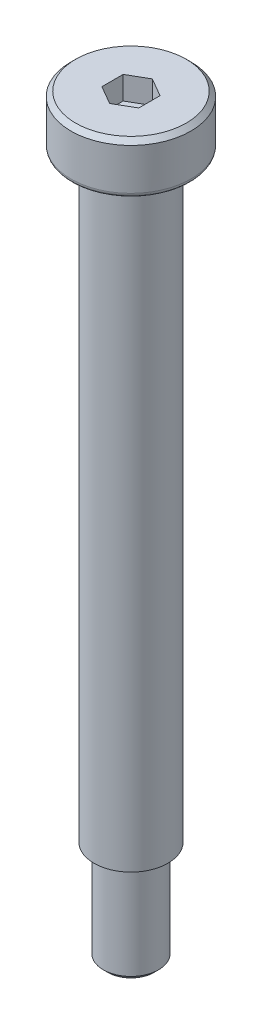
SolidWorks part; units mm, degrees
material "Plain Carbon Steel"
ref_plane "Front Plane" through (0, 0, 0) normal (0, 0, 1) x (1, 0, 0)
ref_plane "Top Plane" through (0, 0, 0) normal (0, 1, 0) x (1, 0, 0)
ref_plane "Right Plane" through (0, 0, 0) normal (1, 0, 0) x (0, 0, -1)
sketch "Sketch1" plane through (0, 0, 0) normal (0, 0, 1) x (1, 0, 0)
  line L0 (0, 0) -> (6.5, 0)
  line L1 (6.5, 0) -> (6.5, -5.5)
  line L2 (6.5, -5.5) -> (3.75, -5.5)
  line L3 (3.75, -5.5) -> (3.75, -5.75)
  line L4 (3.75, -5.75) -> (4, -5.75)
  line L5 (4, -5.75) -> (4, -70.5)
  line L6 (4, -70.5) -> (3, -70.5)
  line L7 (3, -70.5) -> (3, -81.5)
  line L8 (3, -81.5) -> (0, -81.5)
  line L9 (0, -81.5) -> (0, 0)
  line L10 (0, 5) -> (0, -86.5) construction
  dimension "D1" = 5
  dimension "D2" = 5
  dimension "D3" = 6
  dimension "D4" = 8
  dimension "D5" = 0.25
  dimension "D6" = 13
  dimension "Length" = 65
  dimension "D8" = 5.5
  dimension "D9" = 0.25
  dimension "D10" = 11
revolve "Revolve1" add sketch "Sketch1" angle 360 about L10
sketch "Sketch2" plane through (0, 0, 0) normal (0, 1, 0) x (1, 0, 0)
  line L1 (0, -2.3094) -> (2, -1.1547)
  line L2 (2, -1.1547) -> (2, 1.1547)
  line L3 (2, 1.1547) -> (0, 2.3094)
  line L4 (0, 2.3094) -> (-2, 1.1547)
  line L5 (-2, 1.1547) -> (-2, -1.1547)
  line L6 (-2, -1.1547) -> (0, -2.3094)
  circle A0 centre (0, 0) radius 2 construction
  dimension "D1" = 4
extrude "Cut-Extrude1" cut sketch "Sketch2" against normal blind 2.5
chamfer "Chamfer1" distance 0.5 angle 45 1 edges at (-6.5, 0, 0)
fillet "Fillet1" radius 0.5 1 edges at (-6.5, -5.5, 0)
chamfer "Chamfer2" distance 0.5 angle 45 1 edges at (-3, -81.5, 0)
